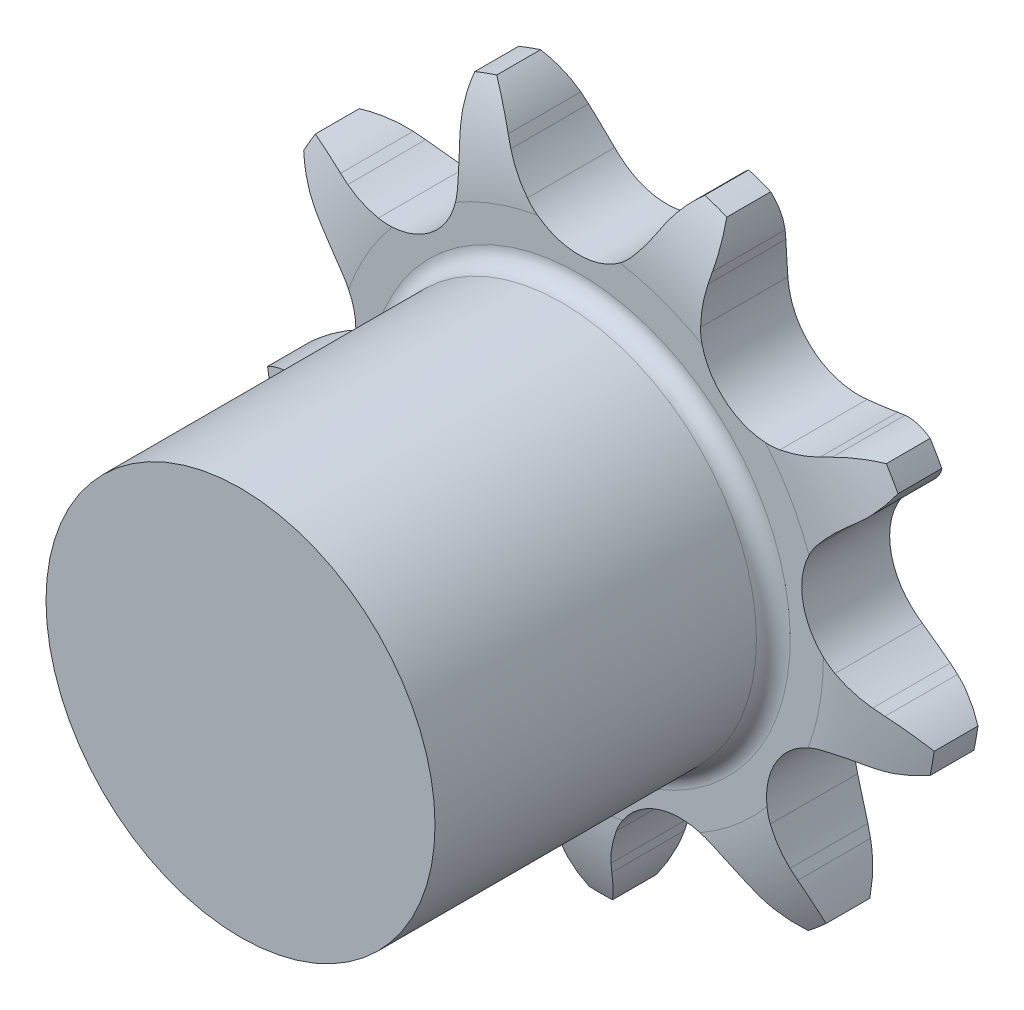
SolidWorks part; units mm, degrees
ref_plane "Front Plane" through (0, 0, 0) normal (0, 0, 1) x (1, 0, 0)
ref_plane "Top Plane" through (0, 0, 0) normal (0, 1, 0) x (1, 0, 0)
ref_plane "Right Plane" through (0, 0, 0) normal (1, 0, 0) x (0, 0, -1)
sketch "Sketch0" plane through (0, 0, 0) normal (0, 0, 1) x (1, 0, 0)
  line L0 (3, -8.2424) -> (0, 0) construction
  line L1 (0, 0) -> (7.5963, -4.3857) construction
  line L2 (0, 0) -> (-3, -8.2424) construction
  line L3 (3, -8.2424) -> (7.5963, -4.3857) construction
  line L4 (3, -8.2424) -> (-3, -8.2424) construction
  line L5 (5.0985, -7.2441) -> (4.8625, -7.0453)
  line L6 (3, -8.2424) -> (0, -9.3343) construction
  line L7 (0.7508, -8.8266) -> (0.8038, -8.5226)
  line L8 (0, -8.2424) -> (0, -10.0424) construction
  line L9 (3.972, -6.4397) -> (1.4813, -11.0591) construction
  line L10 (0, 0) -> (0, -8.2424) construction
  line L11 (4.8625, -7.0453) -> (1.4813, -11.0591) construction
  line L12 (0, -10.0424) -> (0, -10.4354) construction
  line L13 (7.2898, -4.6428) -> (5.0985, -7.2441) construction
  circle A0 centre (0, 0) radius 10.0424 construction
  circle A1 centre (0, 0) radius 8.7714 construction
  arc A2 (-3.6232, -11.4862) -> (10.1587, -6.47) centre (0, 0) ccw
  circle A3 centre (0, 0) radius 10.4354 construction
  circle A4 centre (3, -8.2424) radius 2 construction
  arc A7 (3.972, -6.4397) -> (1.0966, -7.4863) centre (3, -8.2424) ccw
  circle A8 centre (3, -8.2424) radius 2.0481 construction
  arc A9 (5.0985, -7.2441) -> (10.1587, -6.47) centre (7.2898, -4.6428) ccw
  arc A10 (4.8625, -7.0453) -> (3.972, -6.4397) centre (1.4813, -11.0591) ccw
  arc A11 (0.7508, -8.8266) -> (-3.6232, -11.4862) centre (-2.6, -8.2424) cw
  arc A12 (0.8038, -8.5226) -> (1.0966, -7.4863) centre (5.9739, -9.4239) cw
  dimension "D1" = 2.0481
  dimension "R" = 2.0481
sketch "Sketch1" plane through (0, 0, 0) normal (1, 0, 0) x (0, 0, -1)
  line L0 (1.3, 0) -> (-1.3, 0)
  line L1 (-1.3, 0) -> (-1.3, 7.23)
  line L2 (-1.3, 8.7714) -> (0, 8.7714) construction
  line L3 (-0.6, 10.0424) -> (0.6, 10.0424)
  line L5 (1.3, 7.23) -> (1.3, 0)
  line L7 (0, 10.0424) -> (0, 0) construction
  line L8 (-1.3, 7.23) -> (1.3, 7.23) construction
  line L9 (0, 10.0424) -> (0, -10.0424) construction
  line L10 (-1.3, 7.23) -> (-1.3, 10.0424) construction
  line L11 (-1.3, 10.0424) -> (-0.6, 10.0424) construction
  line L12 (0.6, 10.0424) -> (1.3, 10.0424) construction
  line L13 (1.3, 10.0424) -> (1.3, 7.23) construction
  line L14 (0, 0) -> (-6.4008, 0) construction
  line L15 (-1.3, 8.7714) -> (-1.3, 4.6714) construction
  line L22 (1.3, 0) -> (-8.7, 0) construction
  line L24 (-1.3, 0) -> (-1.3, 4.6714) construction
  arc A0 (-0.6, 10.0424) -> (-1.3, 7.23) centre (4.7, 7.23) ccw
  arc A1 (0.6, 10.0424) -> (1.3, 7.23) centre (-4.7, 7.23) cw
  dimension "R" = 6
  dimension "t" = 2.6
  dimension "C" = 0.7
  dimension "A" = 2.8125
  dimension "K" = 6.4008
  dimension "Width" = 10
  dimension "H" = 4.1
revolve "Revolve1" add sketch "Sketch1" angle 360 mid plane about L0
extrude "Cut-Extrude1" cut sketch "Sketch0" against normal through all and the other way through all
pattern_circular "CirPattern1" count 9 over 360 about axis through (0, 0, 0) along (0, 0, 1) of "Cut-Extrude1"
sketch "Sketch2" plane through (0, 0, 0) normal (0, 0, 1) x (1, 0, 0)
  circle A0 centre (0, 0) radius 2.5 construction
  circle A1 centre (0, 0) radius 5.75
  circle A2 centre (0, 0) radius 9.95 construction
  dimension "Bore" = 5
  dimension "Hub Dia." = 11.5
  dimension "OD" = 19.9
extrude "Boss-Extrude1" add sketch "Sketch2" along normal blind 10 from surface at 1.3 starting at face at (0, 0, 1.3)
sketch "Sketch5" plane through (0, 0, 0) normal (0, 0, 1) x (1, 0, 0)
  circle A0 centre (0, 0) radius 9.95 construction
  circle A1 centre (0, 0) radius 9.95
extrude "Cut-Extrude3" cut sketch "Sketch5" against normal through all and the other way through all flip side to cut
fillet "Fillet1" radius 0.5 1 edges at (0, -5.75, 1.3)
equation "\"360/N@Sketch0\" = 360/\"Teeth@CirPattern1\""
equation "\"Ds@Sketch0\" = 1.005 * \"Dr@Sketch0\" + ( 0.003 * 25.4 ) "
equation "\"R@Sketch0\" = 1/2 * \"Ds@Sketch0\""
equation "\"A@Sketch0\" = 35 +  ( 60 / \"Teeth@CirPattern1\" ) "
equation "\"B@Sketch0\" = 18 -  ( 56 / \"Teeth@CirPattern1\" )"
equation "\"ac@Sketch0\" = 0.8 * \"Dr@Sketch0\""
equation "\"ab@Sketch0\" = 1.4 * \"Dr@Sketch0\""
equation "\"J@Sketch0\" = 0.3 * \"Pitch@Sketch0\""
